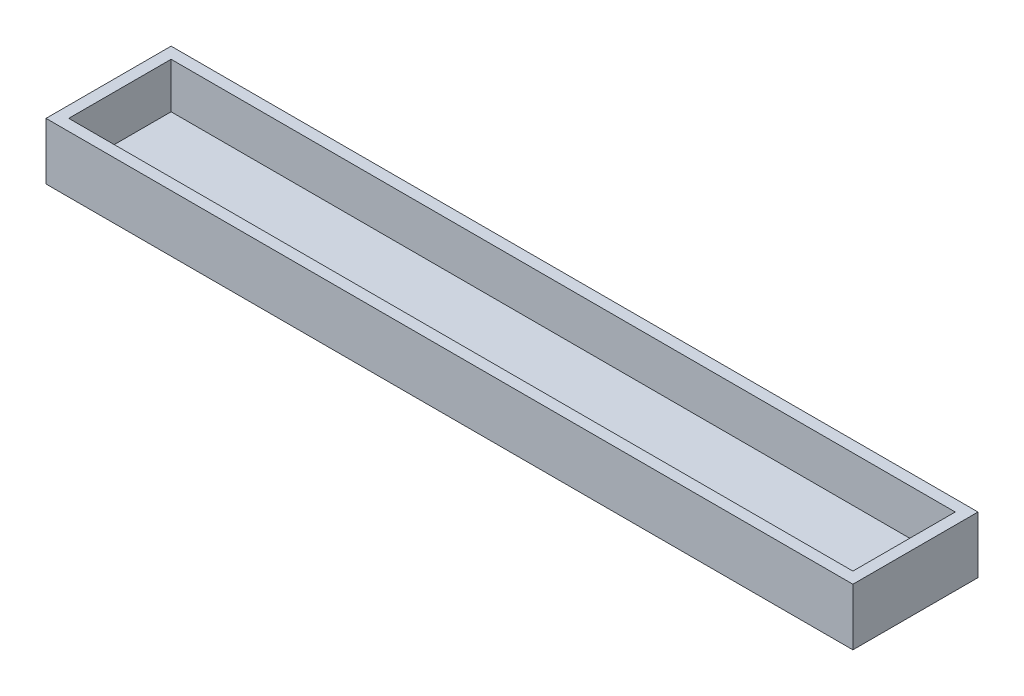
SolidWorks part; units mm, degrees
material "Papel canelado"
ref_plane "Plano frontal" through (0, 0, 0) normal (0, 0, 1) x (1, 0, 0)
ref_plane "Plano superior" through (0, 0, 0) normal (0, 1, 0) x (1, 0, 0)
ref_plane "Plano direito" through (0, 0, 0) normal (1, 0, 0) x (0, 0, -1)
sketch "Esboço1" plane through (0, 0, 0) normal (1, 0, 0) x (0, 0, -1)
  line L1 (0, 0) -> (55, 0)
  line L2 (0, 0) -> (0, 25)
  line L3 (0, 25) -> (55, 25)
  line L4 (55, 0) -> (55, 25)
  dimension "D1" = 55
  dimension "D2" = 25
extrude "Ressalto-extrusão1" add sketch "Esboço1" along normal blind 354.77
shell "Casca1" thickness 5
sketch "Esboço3" plane through (0, 5, 0) normal (0, 1, 0) x (1, 0, 0)
  line L0 (349.77, 50) -> (349.77, 5) construction
  line L1 (349.77, 42.5) -> (345.77, 42.5)
  line L2 (349.77, 42.5) -> (349.77, 12.5)
  line L3 (349.77, 12.5) -> (345.77, 12.5)
  line L4 (345.77, 42.5) -> (345.77, 12.5)
  point P6 (349.77, 27.5)
  dimension "D1" = 4
  dimension "D2" = 30
extrude "Corte-extrusão1" cut sketch "Esboço3" against normal through all
